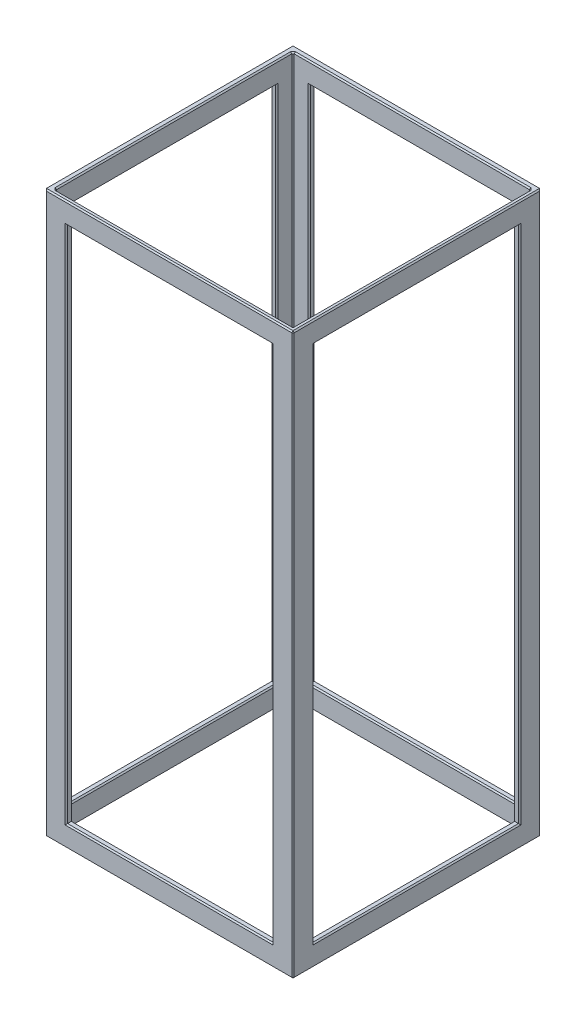
SolidWorks part; units mm, degrees
material "6061-T6 (SS)"
ref_plane "Front Plane" through (0, 0, 0) normal (0, 0, 1) x (1, 0, 0)
ref_plane "Top Plane" through (0, 0, 0) normal (0, 1, 0) x (1, 0, 0)
ref_plane "Right Plane" through (0, 0, 0) normal (1, 0, 0) x (0, 0, -1)
sketch "Sketch2" plane through (0, 0, 0) normal (0, 1, 0) x (1, 0, 0)
  line L1 (-50, 50) -> (50, 50)
  line L2 (-50, 50) -> (-50, -50)
  line L3 (-50, -50) -> (50, -50)
  line L4 (50, 50) -> (50, -50)
  line L5 (-50, 50) -> (50, -50) construction
  line L6 (-50, -50) -> (50, 50) construction
  point P0 (0, 0)
  dimension "D1" = 100
  dimension "D2" = 100
extrude "Boss-Extrude1" add sketch "Sketch2" along normal blind 226.3
shell "Shell1" thickness 2
sketch "Sketch3" plane through (0, 0, 50) normal (0, 0, 1) x (1, 0, 0)
  line L0 (0, 226.3) -> (0, -9.0538) construction
  line L1 (-50, 226.3) -> (50, 226.3) construction
  line L2 (-50, 113.15) -> (59.2409, 113.15) construction
  line L3 (-50, 226.3) -> (-50, 0) construction
  line L4 (50, 226.3) -> (50, 0) construction
  line L5 (-41.5, 217.8) -> (41.5, 217.8)
  line L6 (-41.5, 217.8) -> (-41.5, 8.5)
  line L7 (-41.5, 8.5) -> (41.5, 8.5)
  line L8 (41.5, 217.8) -> (41.5, 8.5)
  line L9 (-41.5, 217.8) -> (41.5, 8.5) construction
  line L10 (-41.5, 8.5) -> (41.5, 217.8) construction
  point P9 (0, 113.15)
  dimension "D1" = 8.5
  dimension "D2" = 8.5
extrude "Cut-Extrude1" cut sketch "Sketch3" against normal through all
sketch "Sketch5" plane through (50, 0, 0) normal (1, 0, 0) x (0, 0, -1)
  line L0 (50, 226.3) -> (50, 0) construction
  line L1 (-41.5, 217.8) -> (41.5, 217.8)
  line L2 (-41.5, 217.8) -> (-41.5, 8.5)
  line L3 (-41.5, 8.5) -> (41.5, 8.5)
  line L4 (41.5, 217.8) -> (41.5, 8.5)
  line L5 (-41.5, 217.8) -> (41.5, 8.5) construction
  line L6 (-41.5, 8.5) -> (41.5, 217.8) construction
  line L7 (-50, 226.3) -> (50, 226.3) construction
  line L8 (-50, 226.3) -> (-50, 0) construction
  line L9 (55, 0) -> (-55, 0) construction
  point P0 (0, 113.15)
  dimension "D1" = 8.5
  dimension "D2" = 8.5
  dimension "D3" = 8.5
  dimension "D4" = 8.5
extrude "Cut-Extrude2" cut sketch "Sketch5" against normal through all
chamfer "Chamfer1" distance 0.5 angle 45 34 edges at (0, 217.8, -48) (-41.5, 113.15, -48) (0, 8.5, -48) (41.5, 113.15, -48) (48, 226.3, 0) (48, 0, 0) (0, 226.3, 48) (0, 0, 48) (0, 226.3, -48) (48, 113.15, -48) (0, 0, -48) (-48, 113.15, 48) (-48, 226.3, 0) (-48, 113.15, -48) (-48, 0, 0) (-48, 217.8, 0) (-48, 113.15, 41.5) (-48, 8.5, 0) (-48, 113.15, -41.5) (-41.5, 113.15, 50) (0, 8.5, 50) (41.5, 113.15, 50) (0, 217.8, 50) (-50, 113.15, 50) (0, 226.3, 50) (0, 0, 50) (50, 113.15, 50) (50, 226.3, 0) (50, 113.15, -50) (50, 0, 0) (50, 113.15, 41.5) (50, 8.5, 0) (50, 113.15, -41.5) (50, 217.8, 0)
